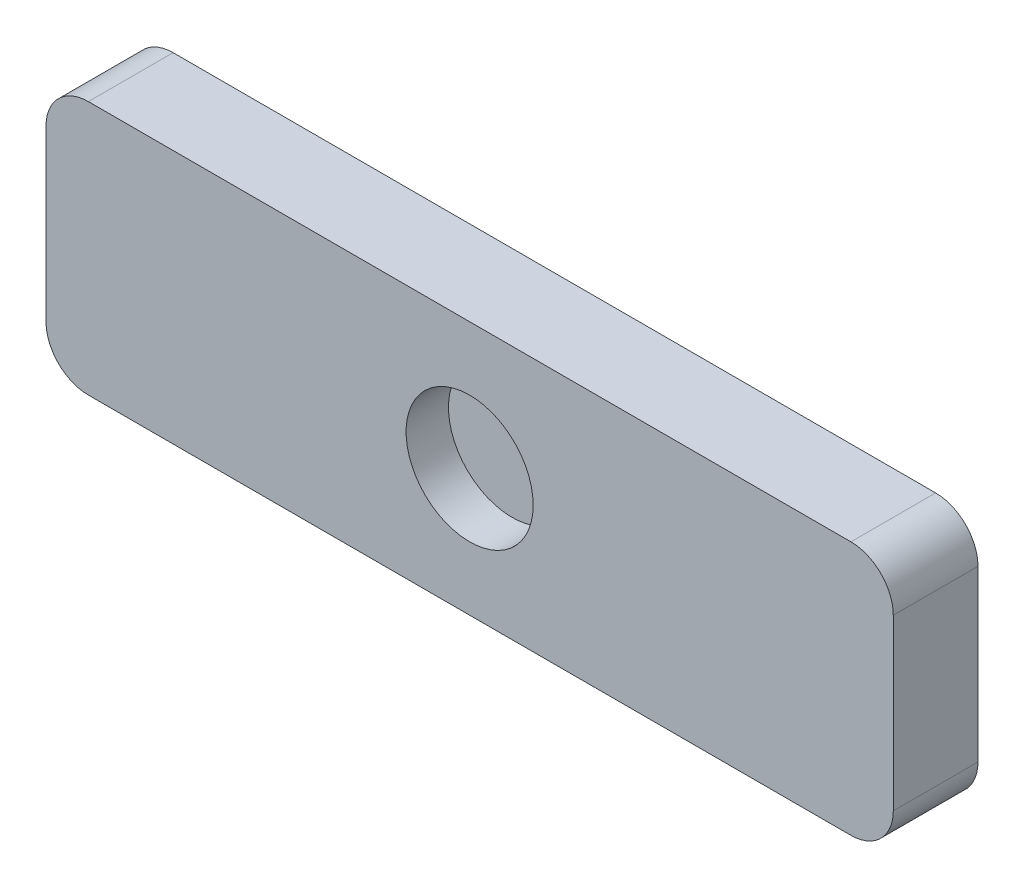
SolidWorks part; units mm, degrees
ref_plane "Front Plane" through (0, 0, 0) normal (0, 0, 1) x (1, 0, 0)
ref_plane "Top Plane" through (0, 0, 0) normal (0, 1, 0) x (1, 0, 0)
ref_plane "Right Plane" through (0, 0, 0) normal (1, 0, 0) x (0, 0, -1)
sketch "Sketch1" plane through (0, 0, 0) normal (0, 0, 1) x (1, 0, 0)
  line L1 (-5000, -1500) -> (5000, -1500)
  line L2 (-5000, -1500) -> (-5000, 1500)
  line L3 (-5000, 1500) -> (5000, 1500)
  line L4 (5000, -1500) -> (5000, 1500)
  line L5 (-5000, -1500) -> (5000, 1500) construction
  line L6 (-5000, 1500) -> (5000, -1500) construction
  point P0 (0, 0)
  dimension "D1" = 5000
  dimension "D2" = 1500
extrude "Boss-Extrude1" add sketch "Sketch1" along normal blind 1000
fillet "Fillet1" radius 500 1 edges at (-5000, 1500, 500)
fillet "Fillet2" radius 500 3 edges at (-5000, -1500, 500) (5000, -1500, 500) (5000, 1500, 500)
sketch "Sketch3" plane through (0, 0, 1000) normal (0, 0, 1) x (1, 0, 0)
  circle A0 centre (0, 0) radius 750
  dimension "D1" = 1500
extrude "Cut-Extrude2" cut sketch "Sketch3" against normal blind 500
